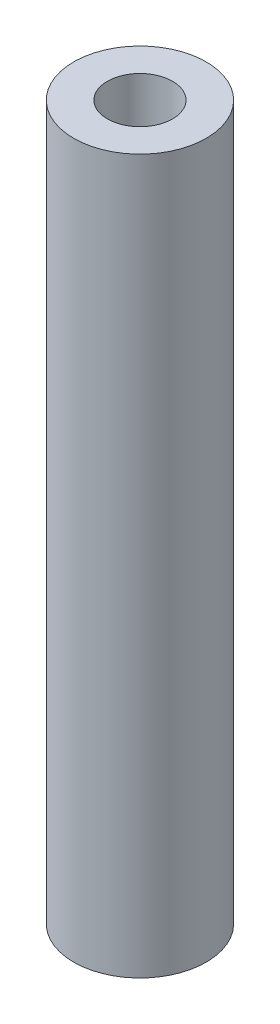
SolidWorks part; units mm, degrees
ref_plane "Front Plane" through (0, 0, 0) normal (0, 0, 1) x (1, 0, 0)
ref_plane "Top Plane" through (0, 0, 0) normal (0, 1, 0) x (1, 0, 0)
ref_plane "Right Plane" through (0, 0, 0) normal (1, 0, 0) x (0, 0, -1)
sketch "Sketch1" plane through (0, 0, 0) normal (0, 1, 0) x (1, 0, 0)
  circle A0 centre (0, 0) radius 1.6
  circle A1 centre (0, 0) radius 3.25
  dimension "D1" = 3.2
  dimension "D2" = 6.5
extrude "Boss-Extrude1" add sketch "Sketch1" along normal blind 35
